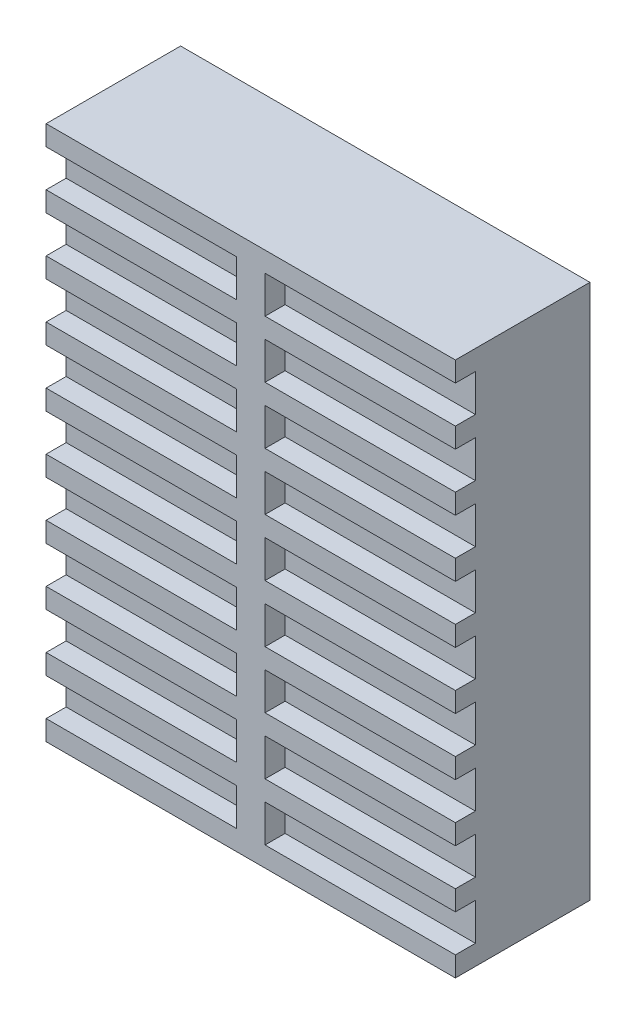
SolidWorks part; units mm, degrees
ref_plane "前视基准面" through (0, 0, 0) normal (0, 0, 1) x (1, 0, 0)
ref_plane "上视基准面" through (0, 0, 0) normal (0, 1, 0) x (1, 0, 0)
ref_plane "右视基准面" through (0, 0, 0) normal (1, 0, 0) x (0, 0, -1)
sketch "草图1" plane through (0, 0, 0) normal (0, 0, 1) x (1, 0, 0)
  line L1 (0, 0) -> (14.3, 0)
  line L2 (0, 0) -> (0, -18.7)
  line L3 (0, -18.7) -> (14.3, -18.7)
  line L4 (14.3, 0) -> (14.3, -18.7)
  dimension "D1" = 18.7
  dimension "D2" = 14.3
extrude "凸台-拉伸1" add sketch "草图1" along normal blind 4
sketch "草图2" plane through (14.3, 0, 0) normal (1, 0, 0) x (0, 0, -1)
  line L0 (-4, -2) -> (-4.7, -2)
  line L1 (-4, 0) -> (-4.7, 0)
  line L2 (-4, 0) -> (-4, -0.7)
  line L3 (-4, -0.7) -> (-4.7, -0.7)
  line L4 (-4.7, 0) -> (-4.7, -0.7)
  line L5 (-4, -2) -> (-4, -2.7)
  line L6 (-4, -2.7) -> (-4.7, -2.7)
  line L7 (-4.7, -2) -> (-4.7, -2.7)
  line L8 (-4, -4) -> (-4.7, -4)
  line L9 (-4, -4) -> (-4, -4.7)
  line L10 (-4, -4.7) -> (-4.7, -4.7)
  line L11 (-4.7, -4) -> (-4.7, -4.7)
  line L12 (-4, -6) -> (-4.7, -6)
  line L13 (-4, -6) -> (-4, -6.7)
  line L14 (-4, -6.7) -> (-4.7, -6.7)
  line L15 (-4.7, -6) -> (-4.7, -6.7)
  line L16 (-4, -8) -> (-4.7, -8)
  line L17 (-4, -8) -> (-4, -8.7)
  line L18 (-4, -8.7) -> (-4.7, -8.7)
  line L19 (-4.7, -8) -> (-4.7, -8.7)
  line L20 (-4, -10) -> (-4.7, -10)
  line L21 (-4, -10) -> (-4, -10.7)
  line L22 (-4, -10.7) -> (-4.7, -10.7)
  line L23 (-4.7, -10) -> (-4.7, -10.7)
  line L24 (-4, -12) -> (-4.7, -12)
  line L25 (-4, -12) -> (-4, -12.7)
  line L26 (-4, -12.7) -> (-4.7, -12.7)
  line L27 (-4.7, -12) -> (-4.7, -12.7)
  line L28 (-4, -14) -> (-4.7, -14)
  line L29 (-4, -14) -> (-4, -14.7)
  line L30 (-4, -14.7) -> (-4.7, -14.7)
  line L31 (-4.7, -14) -> (-4.7, -14.7)
  line L32 (-4, -16) -> (-4.7, -16)
  line L33 (-4, -16) -> (-4, -16.7)
  line L34 (-4, -16.7) -> (-4.7, -16.7)
  line L35 (-4.7, -16) -> (-4.7, -16.7)
  line L36 (-4, -18) -> (-4.7, -18)
  line L37 (-4, -18) -> (-4, -18.7)
  line L38 (-4, -18.7) -> (-4.7, -18.7)
  line L39 (-4.7, -18) -> (-4.7, -18.7)
  dimension "D1" = 0.7
  dimension "D2" = 0.7
  dimension "D3" = 10
extrude "凸台-拉伸2" add sketch "草图2" against normal up to vertex (14.3 mm away)
sketch "草图3" plane through (0, 0, 4) normal (0, 0, 1) x (1, 0, 0)
  line L0 (0, -18.7) -> (14.3, -18.7) construction
  line L1 (6.65, -18.7) -> (7.65, -18.7)
  line L2 (6.65, -18.7) -> (6.65, 0)
  line L3 (6.65, 0) -> (7.65, 0)
  line L4 (7.65, -18.7) -> (7.65, 0)
  line L5 (0, 0) -> (14.3, 0) construction
  line L6 (14.3, -14) -> (14.3, -12.7) construction
  dimension "D1" = 1
  dimension "D2" = 6.65
extrude "凸台-拉伸4" add sketch "草图3" along normal blind 0.7
